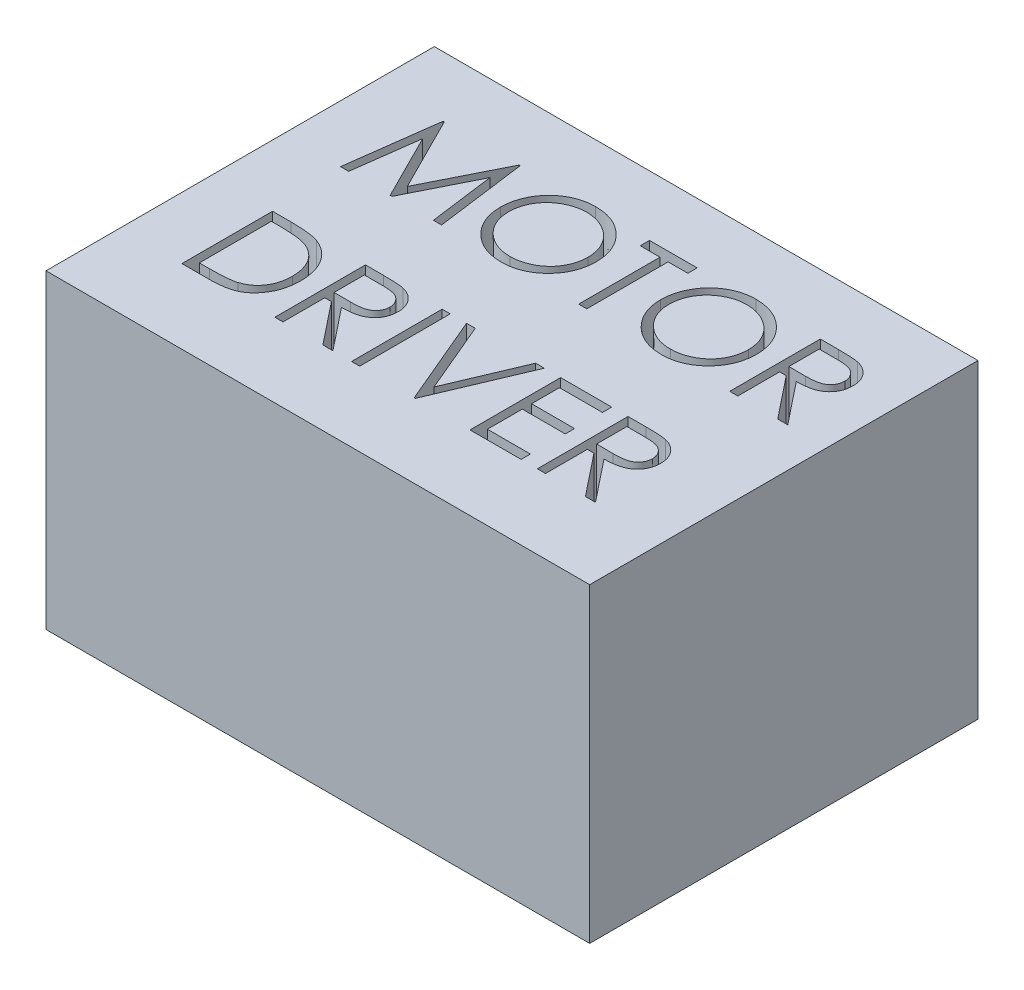
SolidWorks part; units mm, degrees
ref_plane "Front Plane" through (0, 0, 0) normal (0, 0, 1) x (1, 0, 0)
ref_plane "Top Plane" through (0, 0, 0) normal (0, 1, 0) x (1, 0, 0)
ref_plane "Right Plane" through (0, 0, 0) normal (1, 0, 0) x (0, 0, -1)
sketch "Sketch1" plane through (0, 0, 0) normal (0, 1, 0) x (1, 0, 0)
  line L1 (-22.225, -15.875) -> (22.225, -15.875)
  line L2 (-22.225, -15.875) -> (-22.225, 15.875)
  line L3 (-22.225, 15.875) -> (22.225, 15.875)
  line L4 (22.225, -15.875) -> (22.225, 15.875)
  line L5 (-22.225, -15.875) -> (22.225, 15.875) construction
  line L6 (-22.225, 15.875) -> (22.225, -15.875) construction
  point P0 (0, 0)
  dimension "D1" = 44.45
  dimension "D2" = 31.75
extrude "Boss-Extrude1" add sketch "Sketch1" along normal blind 25.4
sketch "Sketch2" plane through (0, 25.4, 0) normal (0, 1, 0) x (1, 0, 0)
  text T0 "MOTOR\r\nDRIVER" font "Century Gothic" height in points 28
extrude "Cut-Extrude1" cut sketch "Sketch2" against normal mid plane 25.4
